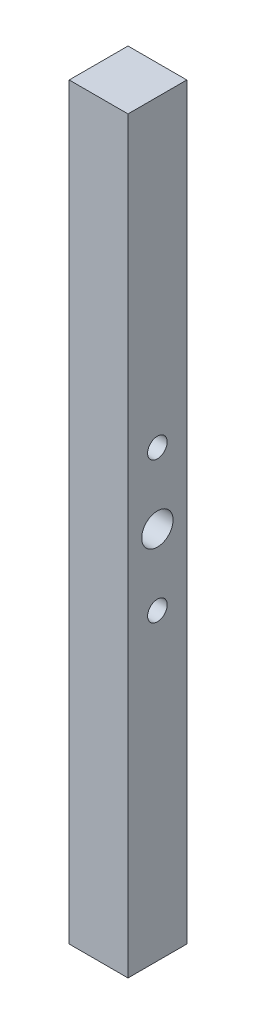
SolidWorks part; units mm, degrees
ref_plane "前视基准面" through (0, 0, 0) normal (0, 0, 1) x (1, 0, 0)
ref_plane "上视基准面" through (0, 0, 0) normal (0, 1, 0) x (1, 0, 0)
ref_plane "右视基准面" through (0, 0, 0) normal (1, 0, 0) x (0, 0, -1)
sketch "草图1" plane through (0, 0, 0) normal (0, 1, 0) x (1, 0, 0)
  line L1 (-7.5, 7.5) -> (7.5, 7.5)
  line L2 (-7.5, 7.5) -> (-7.5, -7.5)
  line L3 (-7.5, -7.5) -> (7.5, -7.5)
  line L4 (7.5, 7.5) -> (7.5, -7.5)
  line L5 (-7.5, 7.5) -> (7.5, -7.5) construction
  line L6 (-7.5, -7.5) -> (7.5, 7.5) construction
  point P0 (0, 0)
  dimension "D1" = 15
  dimension "D2" = 15
extrude "凸台-拉伸1" add sketch "草图1" along normal blind 190.88
sketch "草图2" plane through (7.5, 0, 0) normal (1, 0, 0) x (0, 0, -1)
  line L0 (-7.5, 190.88) -> (-7.5, 0) construction
  circle A0 centre (0, 95.44) radius 4
  circle A1 centre (0, 113.44) radius 2.5
  circle A2 centre (0, 77.44) radius 2.5
  point P5 (-7.5, 95.44)
  dimension "D1" = 8
  dimension "D3" = 5
  dimension "D4" = 5
  dimension "D2" = 7.5
  dimension "D5" = 18
  dimension "D6" = 18
extrude "切除-拉伸1" cut sketch "草图2" against normal through all
